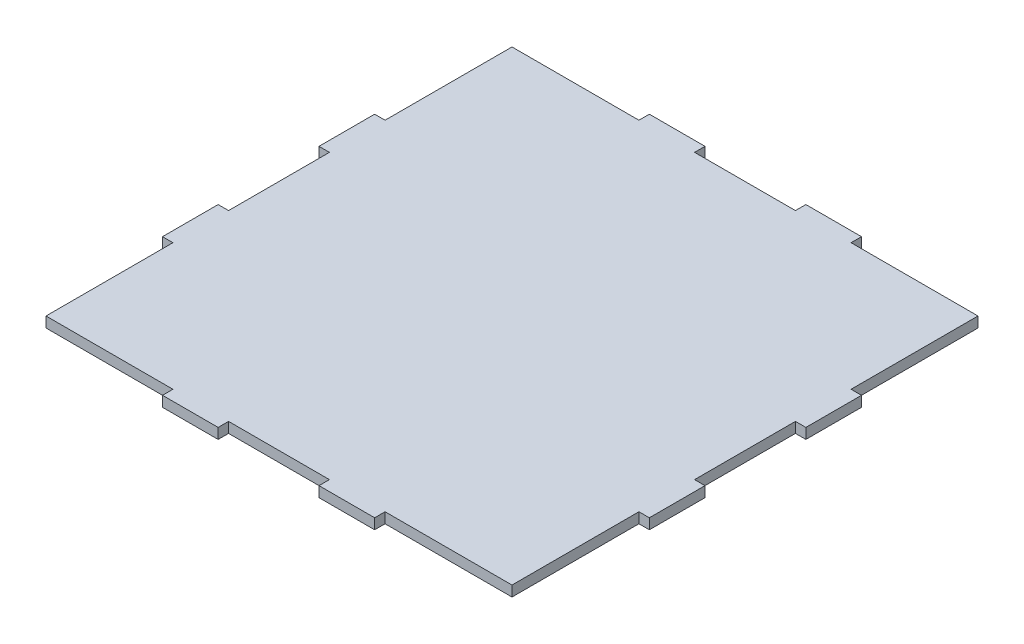
SolidWorks part; units mm, degrees
ref_plane "Front Plane" through (0, 0, 0) normal (0, 0, 1) x (1, 0, 0)
ref_plane "Top Plane" through (0, 0, 0) normal (0, 1, 0) x (1, 0, 0)
ref_plane "Right Plane" through (0, 0, 0) normal (1, 0, 0) x (0, 0, -1)
sketch "Sketch1" plane through (0, 0, 0) normal (0, 1, 0) x (1, 0, 0)
  line L0 (-70, 70) -> (70, -70)
  line L1 (-70, 70) -> (70, 70)
  line L2 (-70, 70) -> (-70, -70)
  line L3 (-70, -70) -> (70, -70)
  line L4 (70, 70) -> (70, -70)
  line L5 (-70, -70) -> (70, 70)
  point P4 (0, 0)
  dimension "D1" = 140
  dimension "D2" = 140
extrude "Boss-Extrude1" add sketch "Sketch1" along normal blind 3 contours L0 L5 L1 | L2 L5 L0 | L5 L3 L0 | L5 L0 L4
sketch "Sketch2" plane through (0, 3, 0) normal (0, 1, 0) x (1, 0, 0)
  line L0 (-70, 70) -> (-70, 67)
  line L1 (-70, 70) -> (-70, -70) construction
  line L2 (-70, 67) -> (-30.5, 67)
  line L3 (-30.5, 67) -> (-30.5, 70)
  line L4 (-70, 70) -> (70, 70) construction
  line L5 (-30.5, 70) -> (-70, 70)
  line L6 (0, -1.65) -> (0, 1.65) construction
  line L7 (30.5, 67) -> (30.5, 70)
  line L8 (70, 67) -> (30.5, 67)
  line L9 (70, 70) -> (70, 67)
  line L10 (30.5, 70) -> (70, 70)
  line L11 (-1.65, 0) -> (1.65, 0) construction
  line L12 (70, -67) -> (30.5, -67)
  line L13 (70, -70) -> (70, -67)
  line L14 (30.5, -70) -> (70, -70)
  line L15 (30.5, -67) -> (30.5, -70)
  line L16 (-30.5, -67) -> (-30.5, -70)
  line L17 (-70, -67) -> (-30.5, -67)
  line L18 (-70, -70) -> (-70, -67)
  line L19 (-30.5, -70) -> (-70, -70)
  line L20 (-67, 30.5) -> (-67, 70)
  line L21 (-67, 70) -> (-70, 70)
  line L22 (-70, 70) -> (-70, 30.5)
  line L23 (-70, 30.5) -> (-67, 30.5)
  line L24 (67, 70) -> (70, 70)
  line L25 (67, 30.5) -> (67, 70)
  line L26 (70, 30.5) -> (67, 30.5)
  line L27 (70, 70) -> (70, 30.5)
  line L28 (67, -70) -> (70, -70)
  line L29 (67, -30.5) -> (67, -70)
  line L30 (70, -30.5) -> (67, -30.5)
  line L31 (70, -70) -> (70, -30.5)
  line L32 (-67, -70) -> (-70, -70)
  line L33 (-67, -30.5) -> (-67, -70)
  line L34 (-70, -30.5) -> (-67, -30.5)
  line L35 (-70, -70) -> (-70, -30.5)
  line L36 (-14.5, 70) -> (-14.5, 67)
  line L37 (-14.5, 67) -> (14.5, 67)
  line L38 (14.5, 67) -> (14.5, 70)
  line L39 (14.5, 70) -> (-14.5, 70)
  line L40 (14.5, -67) -> (14.5, -70)
  line L41 (-14.5, -67) -> (14.5, -67)
  line L42 (-14.5, -70) -> (-14.5, -67)
  line L43 (14.5, -70) -> (-14.5, -70)
  line L44 (70, -14.5) -> (70, 14.5)
  line L45 (-70, 14.5) -> (-67, 14.5)
  line L46 (-67, 14.5) -> (-67, -14.5)
  line L47 (-67, -14.5) -> (-70, -14.5)
  line L48 (-70, -14.5) -> (-70, 14.5)
  line L49 (67, -14.5) -> (70, -14.5)
  line L50 (67, 14.5) -> (67, -14.5)
  line L51 (70, 14.5) -> (67, 14.5)
  dimension "D1" = 39.5
  dimension "D2" = 3
  dimension "D3" = 3
  dimension "D4" = 39.5
  dimension "D5" = 29
  dimension "D6" = 55.5
  dimension "D7" = 29
  dimension "D8" = 55.5
  dimension "D9" = 3
extrude "Cut-Extrude2" cut sketch "Sketch2" against normal blind 3 contours L0 L2 L3 L5 | L22 L23 L20 L21 | L48 L45 L46 L47 | L35 L34 L33 L32 | L18 L17 L16 L19 | L41 L40 L43 L42 | L13 L12 L15 L14 | L31 L30 L29 L28 | L50 L49 L44 L51 | L27 L26 L25 L24 | L9 L8 L7 L10 | L39 L36 L37 L38
